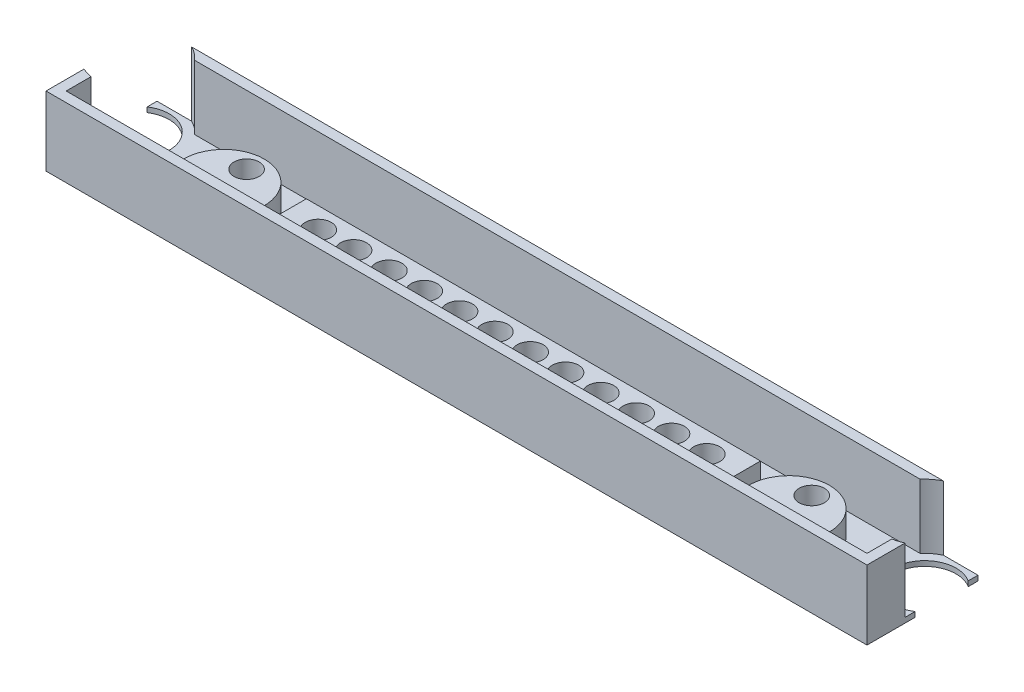
SolidWorks part; units mm, degrees
ref_plane "Front Plane" through (0, 0, 0) normal (0, 0, 1) x (1, 0, 0)
ref_plane "Top Plane" through (0, 0, 0) normal (0, 1, 0) x (1, 0, 0)
ref_plane "Right Plane" through (0, 0, 0) normal (1, 0, 0) x (0, 0, -1)
sketch "Sketch1" plane through (0, 0, 0) normal (0, 1, 0) x (1, 0, 0)
  line L1 (-81.35, -11) -> (81.35, -11)
  line L2 (-81.35, -11) -> (-81.35, 11)
  line L3 (-81.35, 11) -> (81.35, 11)
  line L4 (81.35, -11) -> (81.35, 11)
  line L5 (-81.35, -11) -> (81.35, 11) construction
  line L6 (-81.35, 11) -> (81.35, -11) construction
  point P0 (0, 0)
extrude "Boss-Extrude1" add sketch "Sketch1" along normal blind 13.75
sketch "Sketch2" plane through (0, 13.75, 0) normal (0, 1, 0) x (1, 0, 0)
  line L0 (81.35, 11) -> (-81.35, 11) construction
  line L1 (79.35, -9) -> (-79.35, -9)
  line L2 (79.35, -9) -> (79.35, 9)
  line L3 (79.35, 9) -> (-79.35, 9)
  line L4 (-79.35, -9) -> (-79.35, 9)
  line L5 (-81.35, -11) -> (81.35, -11) construction
  line L6 (81.35, -11) -> (81.35, 11) construction
  line L7 (-81.35, 11) -> (-81.35, -11) construction
  dimension "D1" = 2
  dimension "D2" = 2
  dimension "D3" = 2
  dimension "D4" = 2
extrude "Cut-Extrude1" cut sketch "Sketch2" against normal blind 12.75
sketch "Sketch3" plane through (0, 0, 0) normal (0, -1, 0) x (1, 0, 0)
  circle A2 centre (-3.5, -0.1) radius 2.575
  circle A3 centre (-10.5, -0.1) radius 2.575
  circle A4 centre (-17.5, -0.1) radius 2.575
  circle A5 centre (-24.5, -0.1) radius 2.575
  circle A6 centre (-31.5, -0.1) radius 2.575
  circle A7 centre (-38.5, -0.1) radius 2.575
  circle A8 centre (38.5, -0.1) radius 2.575
  circle A9 centre (31.5, -0.1) radius 2.575
  circle A10 centre (24.5, -0.1) radius 2.575
  circle A11 centre (17.5, -0.1) radius 2.575
  circle A12 centre (10.5, -0.1) radius 2.575
  circle A13 centre (3.5, -0.1) radius 2.575
  dimension "D1" = 5.15
  dimension "D2" = 5.15
  dimension "D3" = 5.15
  dimension "D4" = 5.15
  dimension "D5" = 5.15
  dimension "D6" = 5.15
  dimension "D7" = 5.15
  dimension "D8" = 5.15
  dimension "D9" = 5.15
  dimension "D10" = 5.15
  dimension "D11" = 5.15
  dimension "D12" = 5.15
sketch "Sketch4" plane through (0, 1, 0) normal (0, 1, 0) x (1, 0, 0)
  line L1 (-45, -4.25) -> (45, -4.25)
  line L2 (-45, -4.25) -> (-45, 4.25)
  line L3 (-45, 4.25) -> (45, 4.25)
  line L4 (45, -4.25) -> (45, 4.25)
extrude "Boss-Extrude2" add sketch "Sketch4" along normal blind 5.8
extrude "Cut-Extrude2" cut sketch "Sketch3" against normal through all
sketch "Sketch5" plane through (0, 0, 0) normal (0, -1, 0) x (1, 0, 0)
  circle A0 centre (-77.98, -3.8) radius 6.25
  circle A1 centre (77.98, -3.8) radius 6.25
ref_plane "Plane2" through (0, 13.75, 0) normal (0, 1, 0) x (1, 0, 0)
sketch "Sketch7" plane through (0, 13.75, 0) normal (0, 1, 0) x (1, 0, 0)
  circle A0 centre (-77.98, 3.8) radius 8
  circle A1 centre (77.98, 3.8) radius 8
extrude "Cut-Extrude4" cut sketch "Sketch7" against normal blind 12.75 contours A1 | A0
extrude "Cut-Extrude5" cut sketch "Sketch5" against normal through all
sketch "Sketch8" plane through (0, 1, 0) normal (0, 1, 0) x (1, 0, 0)
  line L0 (-79.35, -9) -> (79.35, -9) construction
  line L1 (71.9005, 9) -> (-71.9005, 9) construction
  line L2 (-45, 4.25) -> (-45, -4.25) construction
  circle A0 centre (-56, -1.1) radius 8
  circle A1 centre (56, -1.1) radius 8
  dimension "D1" = 7.9
  dimension "D2" = 10.1
  dimension "D3" = 11
  dimension "D4" = 7.9
extrude "Boss-Extrude4" add sketch "Sketch8" along normal blind 4.8 contours A1 | A0
sketch "Sketch10" plane through (0, 6.8, 0) normal (0, 1, 0) x (1, 0, 0)
  line L1 (-45, -4.25) -> (45, -4.25)
  line L2 (-45, -4.25) -> (-45, 4.25)
  line L3 (-45, 4.25) -> (45, 4.25)
  line L4 (45, -4.25) -> (45, 4.25)
extrude "Cut-Extrude6" cut sketch "Sketch10" against normal blind 1
sketch "Sketch11" plane through (0, 5.8, 0) normal (0, 1, 0) x (1, 0, 0)
  circle A0 centre (-56, 3.4) radius 2.5
  circle A4 centre (-59.182, -4.282) radius 2.5
  circle A5 centre (-52.818, -4.282) radius 2.5
  circle A6 centre (52.818, -4.282) radius 2.5
  circle A7 centre (59.182, -4.282) radius 2.5
  circle A8 centre (56, 3.4) radius 2.5
extrude "Cut-Extrude7" cut sketch "Sketch11" against normal through all contours A6 | A8 | A7 | A0 | A5 | A4
